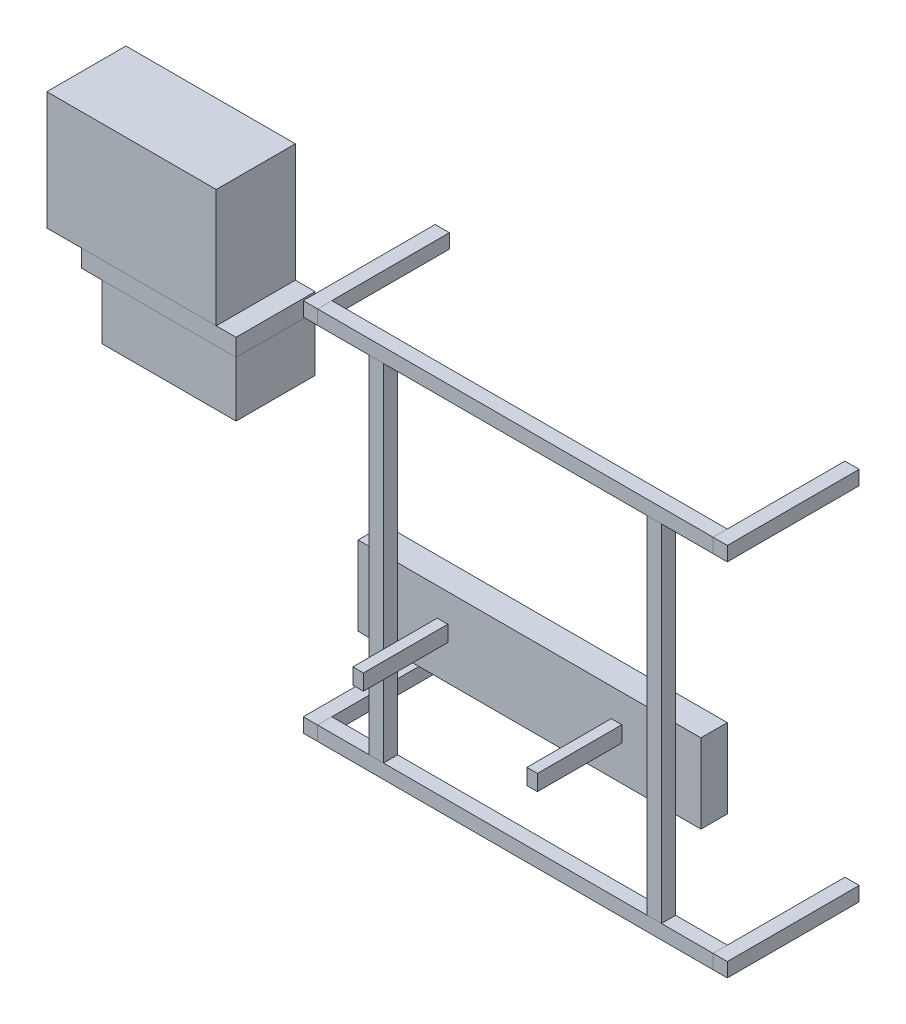
SolidWorks part; units mm, degrees
ref_plane "Front Plane" through (0, 0, 0) normal (0, 0, 1) x (1, 0, 0)
ref_plane "Top Plane" through (0, 0, 0) normal (0, 1, 0) x (1, 0, 0)
ref_plane "Right Plane" through (0, 0, 0) normal (1, 0, 0) x (0, 0, -1)
sketch "Sketch1" plane through (0, 0, 0) normal (0, 0, 1) x (1, 0, 0)
  line L0 (0, -2224.4013) -> (1672.1361, -4479.484)
  line L1 (1672.1361, -4479.484) -> (1672.1361, -6381.7306)
  line L2 (1672.1361, -6381.7306) -> (1181.2338, -6381.7306)
  line L3 (1181.2338, -6381.7306) -> (1181.2338, -7102.7434)
  line L4 (1181.2338, -7102.7434) -> (10615.7633, -7102.7434)
  line L5 (10615.7633, -7102.7434) -> (10615.7633, -1871.5652)
  line L6 (10615.7633, -1871.5652) -> (12303.2402, -1871.5652)
  line L7 (0, 0) -> (0, -2224.4013)
  line L8 (12303.2402, -1871.5652) -> (12303.2402, 0)
  line L9 (0, 0) -> (12303.2402, 0)
sketch "Sketch3" plane through (0, 0, 0) normal (0, 0, 1) x (1, 0, 0)
  line L0 (-3714.5737, 0) -> (-3714.5737, -2231.2583)
  line L1 (-3714.5737, -2231.2583) -> (-3052.5767, -2231.2583)
  line L2 (-3052.5767, -2231.2583) -> (-3052.5767, -2569.7795)
  line L3 (-3052.5767, -2569.7795) -> (-2668.9193, -2569.7795)
  line L4 (-2668.9193, -2569.7795) -> (-2668.9193, -3615.4338)
  line L5 (-2668.9193, -3615.4338) -> (-126.2491, -3615.4338)
  line L6 (-126.2491, -3615.4338) -> (-126.2491, -2238.781)
  line L7 (-126.2491, -2238.781) -> (-502.3837, -2238.781)
  line L8 (-502.3837, -2238.781) -> (-502.3837, 0)
  line L9 (-502.3837, 0) -> (-3714.5737, 0)
sketch "Sketch4" plane through (0, 0, 0) normal (0, 0, 1) x (1, 0, 0)
  line L0 (6422.7586, -8569.5361) -> (6422.7586, -12162.2459)
  line L1 (6422.7586, -12162.2459) -> (7046.3779, -12162.2459)
  line L2 (7046.3779, -12162.2459) -> (7046.3779, -8575.0549)
  line L3 (7046.3779, -8575.0549) -> (6422.7586, -8569.5361)
sketch "Sketch6" plane through (0, 0, 0) normal (0, 0, 1) x (1, 0, 0)
  line L0 (0, 0) -> (0, -2224.4013)
  line L1 (0, -2224.4013) -> (10615.7633, -1871.5652)
  line L2 (10615.7633, -1871.5652) -> (10553.5581, 0)
  line L3 (0, 0) -> (12303.2402, 0) construction
  line L4 (10553.5581, 0) -> (0, 0)
extrude "Boss-Extrude6" [suppressed] add sketch "Sketch6" along normal blind 2500 separate body
sketch "Sketch7" [suppressed] plane through (0, 0, 0) normal (0, 0, 1) x (1, 0, 0)
  line L0 (10553.5581, 0) -> (10615.7633, -1871.5652)
  line L1 (10615.7633, -1871.5652) -> (12303.2402, -1871.5652)
  line L2 (12303.2402, -1871.5652) -> (12303.2402, 0)
  line L3 (12303.2402, 0) -> (10553.5581, 0)
extrude "Boss-Extrude7" [suppressed] add sketch "Sketch7" along normal blind 2500 separate body
sketch "Sketch8" [suppressed] plane through (0, 0, 0) normal (0, 0, 1) x (1, 0, 0)
  line L0 (0, -2224.4013) -> (1672.1361, -4479.484)
  line L1 (1672.1361, -4479.484) -> (10615.7633, -4487.1543)
  line L2 (10615.7633, -7102.7434) -> (10615.7633, -1871.5652) construction
  line L3 (10615.7633, -4487.1543) -> (10615.7633, -1871.5652)
  line L4 (10615.7633, -1871.5652) -> (0, -2224.4013)
extrude "Boss-Extrude8" [suppressed] add sketch "Sketch8" along normal blind 2500 separate body
sketch "Sketch10" [suppressed] plane through (-3.8405, -4478.0466, 0) normal (-0.0009, -1, 0) x (1, -0.0009, 0)
  line L0 (10619.6078, 2500) -> (10619.6078, 0) construction
  line L1 (1675.9773, 2500) -> (10619.6078, 2500)
  line L2 (1675.9773, 2500) -> (1675.9773, 2250)
  line L3 (1675.9773, 2250) -> (10619.6078, 2250)
  line L4 (10619.6078, 2500) -> (10619.6078, 2250)
extrude "Boss-Extrude9" [suppressed] add sketch "Sketch10" along normal blind 2600 separate body
sketch "Sketch11" plane through (0, 0, 0) normal (0, 0, 1) x (1, 0, 0)
  line L1 (-3714.5737, 0) -> (-502.3837, 0)
  line L2 (-3714.5737, 0) -> (-3714.5737, -2238.781)
  line L3 (-3714.5737, -2238.781) -> (-502.3837, -2238.781)
  line L4 (-502.3837, 0) -> (-502.3837, -2238.781)
sketch "Sketch12" plane through (0, 0, 0) normal (0, 0, 1) x (1, 0, 0)
  line L1 (-126.2491, -2238.781) -> (-3052.5767, -2238.781)
  line L2 (-126.2491, -2238.781) -> (-126.2491, -2569.7795)
  line L3 (-126.2491, -2569.7795) -> (-3052.5767, -2569.7795)
  line L4 (-3052.5767, -2238.781) -> (-3052.5767, -2569.7795)
extrude "Boss-Extrude11" add sketch "Sketch12" along normal blind 1500
sketch "Sketch13" plane through (0, 0, 0) normal (0, 0, 1) x (1, 0, 0)
  line L1 (-2668.9193, -2569.7795) -> (-126.2491, -2569.7795)
  line L2 (-2668.9193, -2569.7795) -> (-2668.9193, -3615.4338)
  line L3 (-2668.9193, -3615.4338) -> (-126.2491, -3615.4338)
  line L4 (-126.2491, -2569.7795) -> (-126.2491, -3615.4338)
extrude "Boss-Extrude12" add sketch "Sketch13" along normal blind 1500 separate body
extrude "Boss-Extrude13" add sketch "Sketch11" along normal blind 1500 separate body
sketch "Sketch14" [suppressed] plane through (-3.8405, -4478.0466, 0) normal (-0.0009, -1, 0) x (1, -0.0009, 0)
  line L0 (3284.7204, 2500) -> (3484.7204, 2500)
  line L1 (1675.9773, 2500) -> (10619.6078, 2500) construction
  line L2 (3484.7204, 2500) -> (3484.7204, 2300)
  line L3 (3484.7204, 2300) -> (3284.7204, 2300)
  line L4 (3284.7204, 2300) -> (3284.7204, 2500)
  line L5 (6112.9294, 2500) -> (6112.9294, 0) construction
  line L6 (1675.9773, 0) -> (10619.6078, 0) construction
  line L7 (8941.1385, 2300) -> (8941.1385, 2500)
  line L8 (8741.1385, 2300) -> (8941.1385, 2300)
  line L9 (8741.1385, 2500) -> (8741.1385, 2300)
  line L10 (8941.1385, 2500) -> (8741.1385, 2500)
extrude "Boss-Extrude14" [suppressed] add sketch "Sketch14" along normal blind 2750 separate body
sketch "Sketch15" [suppressed] plane through (0, 0, 2300) normal (0, 0, -1) x (-1, 0, 0)
  line L0 (-3278.5202, -7230.8627) -> (-3278.6917, -7030.8627)
  line L1 (-3278.5202, -7230.8627) -> (-3280.8787, -4480.8637) construction
  line L2 (-3278.6917, -7030.8627) -> (-3478.6918, -7030.8627)
  line L3 (-3478.5201, -7231.0342) -> (-3480.8786, -4481.0352) construction
  line L4 (-3478.6918, -7030.8627) -> (-3478.5201, -7231.0342)
  line L5 (-3478.5201, -7231.0342) -> (-3278.5202, -7230.8627)
  line L6 (-8734.9362, -7235.5423) -> (-8735.1078, -7035.5423)
  line L7 (-8734.9362, -7235.5423) -> (-8737.2947, -4485.5433) construction
  line L8 (-8735.1078, -7035.5423) -> (-8935.1078, -7035.5423)
  line L9 (-8934.9362, -7235.7138) -> (-8937.2947, -4485.7148) construction
  line L10 (-8935.1078, -7035.5423) -> (-8934.9362, -7235.7138)
  line L11 (-8734.9362, -7235.5423) -> (-8934.9362, -7235.7138) construction
  line L12 (-8934.9362, -7235.7138) -> (-8734.9362, -7235.5423)
extrude "Boss-Extrude15" [suppressed] add sketch "Sketch15" along normal blind 2500 separate body
sketch "Sketch17" plane through (0, 0, 0) normal (0, 0, 1) x (1, 0, 0)
  line L0 (0, 0) -> (12303.2402, 0) construction
  line L1 (2147.9627, 0) -> (2417.9627, 0)
  line L2 (2147.9627, 0) -> (2147.9627, -270)
  line L3 (2147.9627, -270) -> (2417.9627, -270)
  line L4 (2417.9627, 0) -> (2417.9627, -270)
  line L5 (9917.9627, 0) -> (10187.9627, 0)
  line L6 (9917.9627, 0) -> (9917.9627, -270)
  line L7 (9917.9627, -270) -> (10187.9627, -270)
  line L8 (10187.9627, 0) -> (10187.9627, -270)
  line L9 (2147.9627, -6832.7434) -> (2417.9627, -6832.7434)
  line L10 (2147.9627, -6832.7434) -> (2147.9627, -7102.7434)
  line L11 (2147.9627, -7102.7434) -> (2417.9627, -7102.7434)
  line L12 (2417.9627, -6832.7434) -> (2417.9627, -7102.7434)
  line L13 (9917.9627, -6832.7434) -> (10187.9627, -6832.7434)
  line L14 (9917.9627, -6832.7434) -> (9917.9627, -7102.7434)
  line L15 (9917.9627, -7102.7434) -> (10187.9627, -7102.7434)
  line L16 (10187.9627, -6832.7434) -> (10187.9627, -7102.7434)
  line L17 (1181.2338, -7102.7434) -> (10615.7633, -7102.7434) construction
  dimension "D1" = 270
  dimension "D2" = 270
  dimension "D3" = 7500
  dimension "D4" = 270
  dimension "D5" = 270
  dimension "D6" = 7500
extrude "Boss-Extrude17" add sketch "Sketch17" along normal blind 2500 separate body
sketch "Sketch18" plane through (0, -270, 0) normal (0, -1, 0) x (1, 0, 0)
  line L0 (2417.9627, 2500) -> (2417.9627, 0) construction
  line L1 (2147.9627, 2500) -> (2417.9627, 2500)
  line L2 (2147.9627, 2500) -> (2147.9627, 2230)
  line L3 (2147.9627, 2230) -> (2417.9627, 2230)
  line L4 (2417.9627, 2500) -> (2417.9627, 2230)
  line L5 (9917.9627, 2500) -> (10187.9627, 2500) construction
  line L6 (9917.9627, 2500) -> (10187.9627, 2500)
  line L7 (9917.9627, 2500) -> (9917.9627, 2230)
  line L8 (9917.9627, 2230) -> (10187.9627, 2230)
  line L9 (10187.9627, 2500) -> (10187.9627, 2230)
  line L10 (10187.9627, 2500) -> (10187.9627, 0) construction
  line L11 (9917.9627, 2500) -> (9917.9627, 0) construction
sketch "Sketch19" plane through (9917.9627, 0, 0) normal (-1, 0, 0) x (0, 0, 1)
  line L0 (2500, 0) -> (2500, -270) construction
  line L1 (2500, 0) -> (2230, 0)
  line L2 (2500, 0) -> (2500, -270)
  line L3 (2500, -270) -> (2230, -270)
  line L4 (2230, 0) -> (2230, -270)
  line L5 (2500, -270) -> (0, -270) construction
  line L7 (2500, -6832.7434) -> (2230, -6832.7434)
  line L8 (2500, -6832.7434) -> (2500, -7102.7434)
  line L9 (2500, -7102.7434) -> (2230, -7102.7434)
  line L10 (2230, -6832.7434) -> (2230, -7102.7434)
extrude "Boss-Extrude19" add sketch "Sketch19" along normal up to next (7500 mm away) separate body
sketch "Sketch20" plane through (0, -270, 0) normal (0, -1, 0) x (1, 0, 0)
  line L0 (6167.9627, 2500) -> (6167.9627, 2230) construction
  line L1 (2417.9627, 2500) -> (9917.9627, 2500) construction
  line L2 (2417.9627, 2230) -> (9917.9627, 2230) construction
  line L3 (8667.9627, 2500) -> (8937.9627, 2500)
  line L4 (3397.9627, 2500) -> (3667.9627, 2500)
  line L5 (3397.9627, 2500) -> (3397.9627, 2230)
  line L6 (3397.9627, 2230) -> (3667.9627, 2230)
  line L7 (3667.9627, 2500) -> (3667.9627, 2230)
  line L8 (8667.9627, 2500) -> (8667.9627, 2230)
  line L9 (8667.9627, 2230) -> (8937.9627, 2230)
  line L10 (8937.9627, 2500) -> (8937.9627, 2230)
  dimension "D1" = 270
  dimension "D2" = 2500
  dimension "D3" = 270
  dimension "D4" = 2500
extrude "Boss-Extrude20" add sketch "Sketch20" along normal up to next (6562.7434 mm away) separate body
sketch "Sketch21" plane through (0, 0, 2230) normal (0, 0, -1) x (-1, 0, 0)
  line L0 (-3397.9627, -6832.7434) -> (-3397.9627, -270) construction
  line L1 (-9417.1198, -3679.7526) -> (-2917.1198, -3679.7526)
  line L2 (-9417.1198, -3679.7526) -> (-9417.1198, -5179.7526)
  line L3 (-9417.1198, -5179.7526) -> (-2917.1198, -5179.7526)
  line L4 (-2917.1198, -3679.7526) -> (-2917.1198, -5179.7526)
  dimension "D1" = 6500
  dimension "D2" = 1500
  dimension "D3" = 480.8429
extrude "Boss-Extrude21" add sketch "Sketch21" along normal blind 500 separate body
sketch "Sketch23" plane through (0, 0, 2230) normal (0, 0, 1) x (1, 0, 0)
  line L0 (3667.9627, -6832.7434) -> (3667.9627, -270) construction
  line L1 (4417.9627, -4213.7042) -> (4617.9627, -4213.7042)
  line L2 (4417.9627, -4213.7042) -> (4417.9627, -4513.7042)
  line L3 (4417.9627, -4513.7042) -> (4617.9627, -4513.7042)
  line L4 (4617.9627, -4213.7042) -> (4617.9627, -4513.7042)
  line L5 (7717.9627, -4213.7042) -> (7917.9627, -4213.7042)
  line L6 (7717.9627, -4213.7042) -> (7717.9627, -4513.7042)
  line L7 (7717.9627, -4513.7042) -> (7917.9627, -4513.7042)
  line L8 (7917.9627, -4213.7042) -> (7917.9627, -4513.7042)
  line L9 (8667.9627, -6832.7434) -> (8667.9627, -270) construction
  dimension "D1" = 200
  dimension "D2" = 300
  dimension "D3" = 750
  dimension "D4" = 200
  dimension "D5" = 300
  dimension "D6" = 750
extrude "Boss-Extrude22" add sketch "Sketch23" along normal blind 1600 separate body
